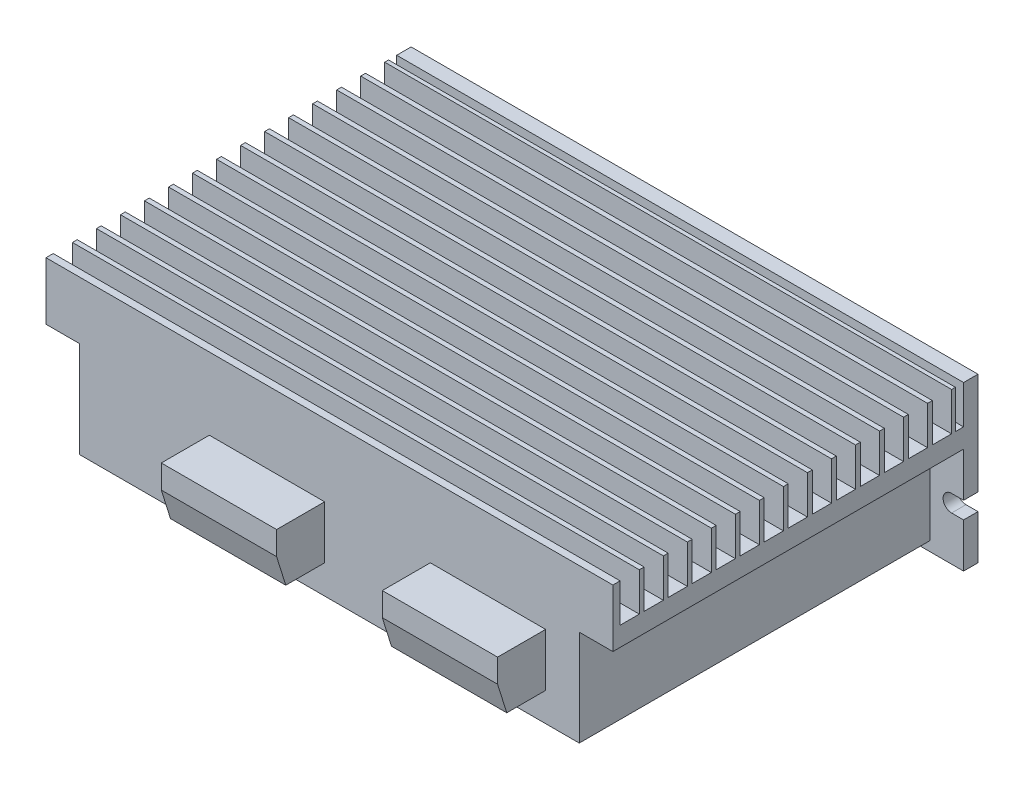
SolidWorks part; units mm, degrees
ref_plane "Спереди" through (0, 0, 0) normal (0, 0, 1) x (1, 0, 0)
ref_plane "Сверху" through (0, 0, 0) normal (0, 1, 0) x (1, 0, 0)
ref_plane "Справа" through (0, 0, 0) normal (1, 0, 0) x (0, 0, -1)
sketch "Эскиз1" plane through (0, 0, 0) normal (0, 0, 1) x (1, 0, 0)
  line L0 (-49.2063, -23.7932) -> (54.7937, -23.7932)
  line L1 (-49.2063, -23.7932) -> (-49.2063, -1.7932)
  line L3 (54.7937, -1.7932) -> (54.7937, -23.7932)
  line L4 (-49.2063, -1.7932) -> (-56.2063, -1.7932)
  line L5 (-56.2063, -1.7932) -> (-56.2063, 10.2068)
  line L6 (-56.2063, 10.2068) -> (61.7937, 10.2068)
  line L7 (61.7937, 10.2068) -> (61.7937, -1.7932)
  line L8 (61.7937, -1.7932) -> (54.7937, -1.7932)
  dimension "D1" = 104
  dimension "D2" = 12
  dimension "D3" = 34
  dimension "D4" = 118
  dimension "D5" = 7
extrude "Бобышка-Вытянуть1" add sketch "Эскиз1" along normal blind 73
sketch "Эскиз2" plane through (0, 0, 0) normal (0, 0, -1) x (-1, 0, 0)
  line L1 (-61.7937, 10.2068) -> (56.2063, 10.2068)
  line L2 (-61.7937, 10.2068) -> (-61.7937, -23.7932)
  line L3 (-61.7937, -23.7932) -> (56.2063, -23.7932)
  line L4 (56.2063, 10.2068) -> (56.2063, -23.7932)
extrude "Бобышка-Вытянуть2" add sketch "Эскиз2" along normal blind 3
sketch "Эскиз3" plane through (61.7937, 0, 0) normal (1, 0, 0) x (0, 0, -1)
  line L0 (-73, 2.2068) -> (10.9439, 2.2068) construction
  line L1 (-73, -1.7932) -> (-73, 10.2068) construction
  line L2 (-73, 10.2068) -> (3, 10.2068) construction
  line L4 (-71.5, 10.2068) -> (-67.5, 10.2068)
  line L5 (-71.5, 10.2068) -> (-71.5, 2.2068)
  line L6 (-71.5, 2.2068) -> (-67.5, 2.2068)
  line L7 (-67.5, 10.2068) -> (-67.5, 2.2068)
  line L8 (-66.5, 10.2068) -> (-62.5, 10.2068)
  line L9 (-66.5, 10.2068) -> (-66.5, 2.2068)
  line L10 (-66.5, 2.2068) -> (-62.5, 2.2068)
  line L11 (-62.5, 10.2068) -> (-62.5, 2.2068)
  line L12 (-61.5, 10.2068) -> (-57.5, 10.2068)
  line L13 (-61.5, 10.2068) -> (-61.5, 2.2068)
  line L14 (-61.5, 2.2068) -> (-57.5, 2.2068)
  line L15 (-57.5, 10.2068) -> (-57.5, 2.2068)
  line L16 (-56.5, 10.2068) -> (-52.5, 10.2068)
  line L17 (-56.5, 10.2068) -> (-56.5, 2.2068)
  line L18 (-56.5, 2.2068) -> (-52.5, 2.2068)
  line L19 (-52.5, 10.2068) -> (-52.5, 2.2068)
  line L20 (-51.5, 10.2068) -> (-47.5, 10.2068)
  line L21 (-51.5, 10.2068) -> (-51.5, 2.2068)
  line L22 (-51.5, 2.2068) -> (-47.5, 2.2068)
  line L23 (-47.5, 10.2068) -> (-47.5, 2.2068)
  line L24 (-46.5, 10.2068) -> (-42.5, 10.2068)
  line L25 (-46.5, 10.2068) -> (-46.5, 2.2068)
  line L26 (-46.5, 2.2068) -> (-42.5, 2.2068)
  line L27 (-42.5, 10.2068) -> (-42.5, 2.2068)
  line L28 (-41.5, 10.2068) -> (-37.5, 10.2068)
  line L29 (-41.5, 10.2068) -> (-41.5, 2.2068)
  line L30 (-41.5, 2.2068) -> (-37.5, 2.2068)
  line L31 (-37.5, 10.2068) -> (-37.5, 2.2068)
  line L32 (-36.5, 10.2068) -> (-32.5, 10.2068)
  line L33 (-36.5, 10.2068) -> (-36.5, 2.2068)
  line L34 (-36.5, 2.2068) -> (-32.5, 2.2068)
  line L35 (-32.5, 10.2068) -> (-32.5, 2.2068)
  line L36 (-31.5, 10.2068) -> (-27.5, 10.2068)
  line L37 (-31.5, 10.2068) -> (-31.5, 2.2068)
  line L38 (-31.5, 2.2068) -> (-27.5, 2.2068)
  line L39 (-27.5, 10.2068) -> (-27.5, 2.2068)
  line L40 (-26.5, 10.2068) -> (-22.5, 10.2068)
  line L41 (-26.5, 10.2068) -> (-26.5, 2.2068)
  line L42 (-26.5, 2.2068) -> (-22.5, 2.2068)
  line L43 (-22.5, 10.2068) -> (-22.5, 2.2068)
  line L44 (-21.5, 10.2068) -> (-17.5, 10.2068)
  line L45 (-21.5, 10.2068) -> (-21.5, 2.2068)
  line L46 (-21.5, 2.2068) -> (-17.5, 2.2068)
  line L47 (-17.5, 10.2068) -> (-17.5, 2.2068)
  line L48 (-16.5, 10.2068) -> (-12.5, 10.2068)
  line L49 (-16.5, 10.2068) -> (-16.5, 2.2068)
  line L50 (-16.5, 2.2068) -> (-12.5, 2.2068)
  line L51 (-12.5, 10.2068) -> (-12.5, 2.2068)
  line L52 (-11.5, 10.2068) -> (-7.5, 10.2068)
  line L53 (-11.5, 10.2068) -> (-11.5, 2.2068)
  line L54 (-11.5, 2.2068) -> (-7.5, 2.2068)
  line L55 (-7.5, 10.2068) -> (-7.5, 2.2068)
  line L56 (-6.5, 10.2068) -> (-2.5, 10.2068)
  line L57 (-6.5, 10.2068) -> (-6.5, 2.2068)
  line L58 (-6.5, 2.2068) -> (-2.5, 2.2068)
  line L59 (-2.5, 10.2068) -> (-2.5, 2.2068)
  line L60 (0, 2.2068) -> (-1.7015, 2.2068)
  line L61 (0, 2.2068) -> (0, 10.2068)
  line L62 (0, 10.2068) -> (-1.7015, 10.2068)
  line L63 (-1.7015, 2.2068) -> (-1.7015, 10.2068)
  dimension "D1" = 8
  dimension "D2" = 4
  dimension "D3" = 4
  dimension "D4" = 4
  dimension "D5" = 4
  dimension "D6" = 4
  dimension "D7" = 4
  dimension "D8" = 4
  dimension "D9" = 4
  dimension "D10" = 4
  dimension "D11" = 4
  dimension "D12" = 4
  dimension "D13" = 4
  dimension "D14" = 1.5
  dimension "D15" = 1
  dimension "D16" = 1
  dimension "D17" = 1
  dimension "D18" = 1
  dimension "D19" = 1
  dimension "D20" = 1
  dimension "D21" = 1
  dimension "D22" = 1
  dimension "D23" = 1
  dimension "D24" = 1
  dimension "D25" = 1
  dimension "D26" = 4
  dimension "D27" = 4
  dimension "D29" = 1
  dimension "D30" = 1
extrude "Вырез-Вытянуть1" cut sketch "Эскиз3" against normal blind 122
sketch "Эскиз4" plane through (0, 0, 73) normal (0, 0, 1) x (1, 0, 0)
  line L0 (-49.2063, -23.7932) -> (54.7937, -23.7932) construction
  line L1 (23.7937, -4.7932) -> (47.7937, -4.7932)
  line L2 (23.7937, -4.7932) -> (23.7937, -15.7932)
  line L3 (23.7937, -15.7932) -> (47.7937, -15.7932)
  line L4 (47.7937, -4.7932) -> (47.7937, -15.7932)
  line L6 (-22.2063, -4.7932) -> (1.7937, -4.7932)
  line L7 (-22.2063, -4.7932) -> (-22.2063, -15.7932)
  line L8 (-22.2063, -15.7932) -> (1.7937, -15.7932)
  line L9 (1.7937, -4.7932) -> (1.7937, -15.7932)
  line L11 (54.7937, -23.7932) -> (54.7937, -1.7932) construction
  dimension "D1" = 24
  dimension "D2" = 11
  dimension "D3" = 19
  dimension "D4" = 24
  dimension "D5" = 11
  dimension "D6" = 22
  dimension "D7" = 7
extrude "Бобышка-Вытянуть3" add sketch "Эскиз4" along normal blind 10
sketch "Эскиз5" plane through (-22.2063, 0, 0) normal (-1, 0, 0) x (0, 0, 1)
  line L0 (83, -4.7932) -> (83, -9.6814)
  line L1 (83, -4.7932) -> (83, -15.7932) construction
  line L2 (83, -9.6814) -> (81.0845, -15.7932)
  line L3 (83, -15.7932) -> (73, -15.7932) construction
  line L4 (81.0845, -15.7932) -> (84.8188, -15.7932)
  line L5 (84.8188, -15.7932) -> (84.8188, -4.7932)
  line L6 (84.8188, -4.7932) -> (83, -4.7932)
extrude "Вырез-Вытянуть2" cut sketch "Эскиз5" against normal blind 72
sketch "Эскиз6" plane through (0, 0, -3) normal (0, 0, -1) x (-1, 0, 0)
  line L0 (-61.7937, -12.7932) -> (56.2063, -12.7932) construction
  line L1 (-61.7937, 10.2068) -> (-61.7937, -23.7932) construction
  line L2 (56.2063, -23.7932) -> (56.2063, 10.2068) construction
  line L3 (-61.7937, -23.7932) -> (56.2063, -23.7932) construction
  line L4 (-2.7937, -12.7932) -> (-2.7937, -23.7932) construction
  line L5 (-59.2937, -11.0246) -> (-61.7937, -11.0246)
  line L6 (-59.2937, -14.5618) -> (-61.7937, -14.5618)
  line L7 (-61.7937, -14.5618) -> (-61.7937, -11.0246)
  line L8 (53.7063, -10.7646) -> (56.2063, -10.7646)
  line L9 (53.7063, -14.8217) -> (56.2063, -14.8217)
  line L10 (56.2063, -14.8217) -> (56.2063, -10.7646)
  arc A0 (-59.2937, -14.5618) -> (-59.2937, -11.0246) centre (-59.2937, -12.7932) ccw
  arc A1 (53.7063, -10.7646) -> (53.7063, -14.8217) centre (53.7063, -12.7932) ccw
  dimension "D2" = 113
  dimension "D3" = 56.5
  dimension "D1" = 11
extrude "Вырез-Вытянуть3" cut sketch "Эскиз6" against normal blind 5
chamfer "Фаска1" distance 2 angle 45 3 edges at (2.7937, -23.7932, 73)
